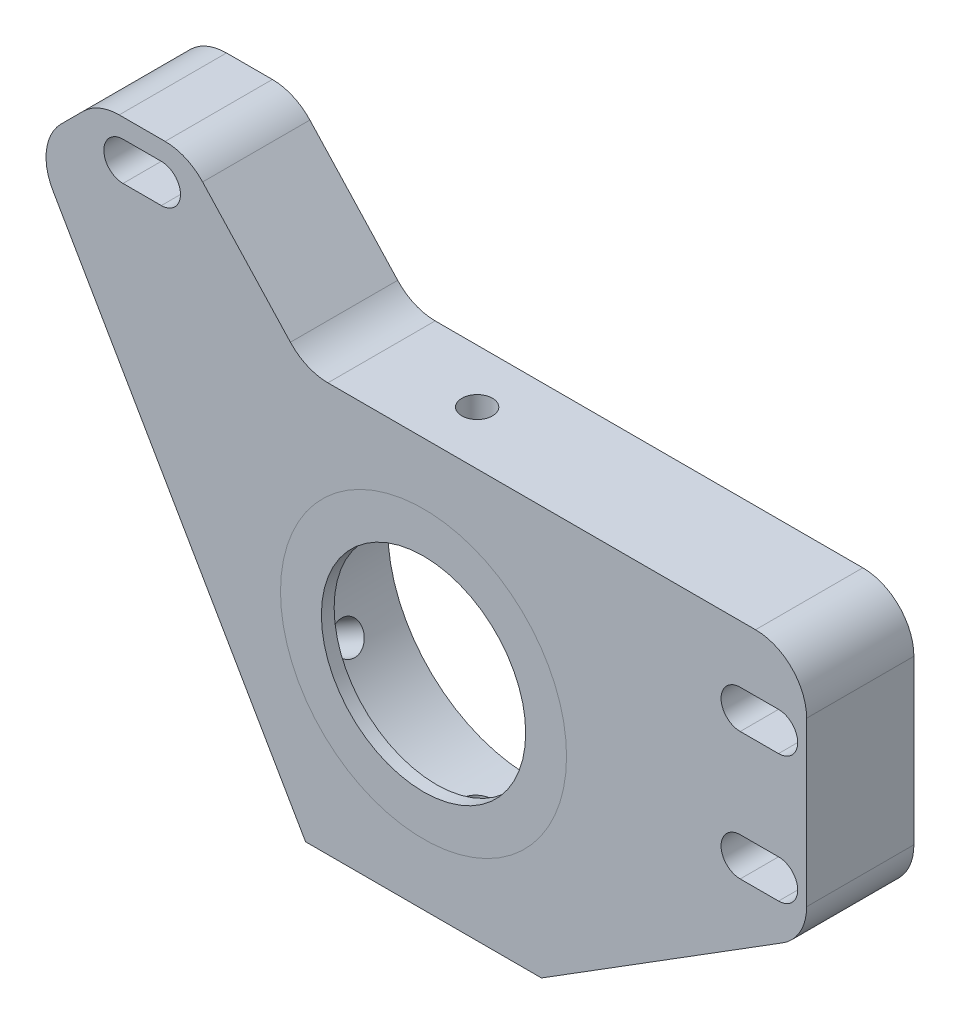
SolidWorks part; units mm, degrees
ref_plane "Płaszczyzna przednia" through (0, 0, 0) normal (0, 0, 1) x (1, 0, 0)
ref_plane "Płaszczyzna górna" through (0, 0, 0) normal (0, 1, 0) x (1, 0, 0)
ref_plane "Płaszczyzna prawa" through (0, 0, 0) normal (1, 0, 0) x (0, 0, -1)
sketch "Szkic1" plane through (0, 0, 0) normal (0, 0, 1) x (1, 0, 0)
  line L0 (9.2376, 16) -> (30, 16)
  line L1 (-9.2376, 16) -> (-18.4752, 0)
  line L2 (-18.4752, 0) -> (-9.2376, -16)
  line L3 (-9.2376, -16) -> (9.2376, -16)
  line L4 (9.2376, -16) -> (18.4752, 0)
  line L5 (18.4752, 0) -> (9.2376, 16)
  line L6 (9.2376, 16) -> (-9.2376, 16)
  line L7 (30, 16) -> (30, -16)
  line L8 (30, -16) -> (9.2376, -16)
  line L9 (9.2376, -16) -> (30, -3)
  line L10 (-18.4752, 0) -> (-33.4863, 26)
  line L11 (-33.4863, 26) -> (-18.4863, 26)
  line L12 (-18.4863, 26) -> (-9.2376, 16)
  circle A0 centre (0, 0) radius 16 construction
  dimension "D1" = 32
  dimension "D2" = 30
  dimension "D6" = 13
  dimension "D7" = 42
  dimension "D8" = 15
extrude "Dodanie-wyciągnięcie1" add sketch "Szkic1" along normal blind 8.4
sketch "Szkic2" plane through (0, 0, 8.4) normal (0, 0, 1) x (1, 0, 0)
  circle A0 centre (0, 0) radius 11.2
  dimension "D1" = 22.4
extrude "Wytnij-wyciągnięcie1" cut sketch "Szkic2" against normal through all
sketch "Szkic3" plane through (0, 16, 0) normal (0, 1, 0) x (1, 0, 0)
  line L0 (-9.2376, -8.4) -> (-9.2376, 0) construction
  circle A0 centre (0, -4.2) radius 1.2
  point P4 (-9.2376, -4.2)
  dimension "D1" = 2.4
extrude "Wytnij-wyciągnięcie2" cut sketch "Szkic3" against normal through all
sketch "Szkic4" plane through (-13.8564, -8, 0) normal (-0.866, -0.5, 0) x (0, 0, 1)
  line L0 (8.4, -9.2376) -> (0, -9.2376) construction
  circle A0 centre (4.2, 0.9816) radius 1.2
  point P4 (4.2, -9.2376)
  dimension "D1" = 2.4
extrude "Wytnij-wyciągnięcie3" cut sketch "Szkic4" against normal blind 10
sketch "Szkic5" plane through (0, 0, 8.4) normal (0, 0, 1) x (1, 0, 0)
  circle A0 centre (0, 0) radius 8
  circle A1 centre (0, 0) radius 11.2 construction
  circle A2 centre (0, 0) radius 11.2
  dimension "D1" = 16
extrude "Dodanie-wyciągnięcie2" add sketch "Szkic5" against normal blind 1 separate body
chamfer "Sfazowanie1" distance 8 angle 45 1 edges at (-33.4863, 26, 4.2)
fillet "Zaokrąglenie2" radius 4 6 edges at (30, -3, 4.2) (30, 16, 4.2) (-9.2376, 16, 4.2) (-18.4863, 26, 4.2) (-30.5581, 20.9282, 4.2) (-25.4863, 26, 4.2)
sketch "Szkic6" plane through (0, 0, 8.4) normal (0, 0, 1) x (1, 0, 0)
  line L0 (24.8, 0) -> (27.8, 0) construction
  line L1 (24.8, 1.5) -> (27.8, 1.5)
  line L2 (24.8, -1.5) -> (27.8, -1.5)
  line L3 (24.8, 10) -> (27.8, 10) construction
  line L4 (24.8, 11.5) -> (27.8, 11.5)
  line L5 (24.8, 8.5) -> (27.8, 8.5)
  line L6 (-23.5324, 23) -> (-20.5324, 23) construction
  line L7 (-23.5324, 24.5) -> (-20.5324, 24.5)
  line L8 (-23.5324, 21.5) -> (-20.5324, 21.5)
  line L9 (-23.8295, 26) -> (-20.2353, 26) construction
  arc A0 (24.8, 1.5) -> (24.8, -1.5) centre (24.8, 0) ccw
  arc A1 (27.8, -1.5) -> (27.8, 1.5) centre (27.8, 0) ccw
  arc A2 (24.8, 11.5) -> (24.8, 8.5) centre (24.8, 10) ccw
  arc A3 (27.8, 8.5) -> (27.8, 11.5) centre (27.8, 10) ccw
  arc A4 (-23.5324, 24.5) -> (-23.5324, 21.5) centre (-23.5324, 23) ccw
  arc A5 (-20.5324, 21.5) -> (-20.5324, 24.5) centre (-20.5324, 23) ccw
  point P3 (26.3, 0)
  point P8 (26.3, 10)
  point P15 (-22.0324, 23)
  point P24 (-22.0324, 26)
  dimension "D3" = 1.5
  dimension "D1" = 26.3
  dimension "D2" = 3
  dimension "D4" = 10
  dimension "D5" = 3
extrude "Wytnij-wyciągnięcie4" cut sketch "Szkic6" against normal through all
